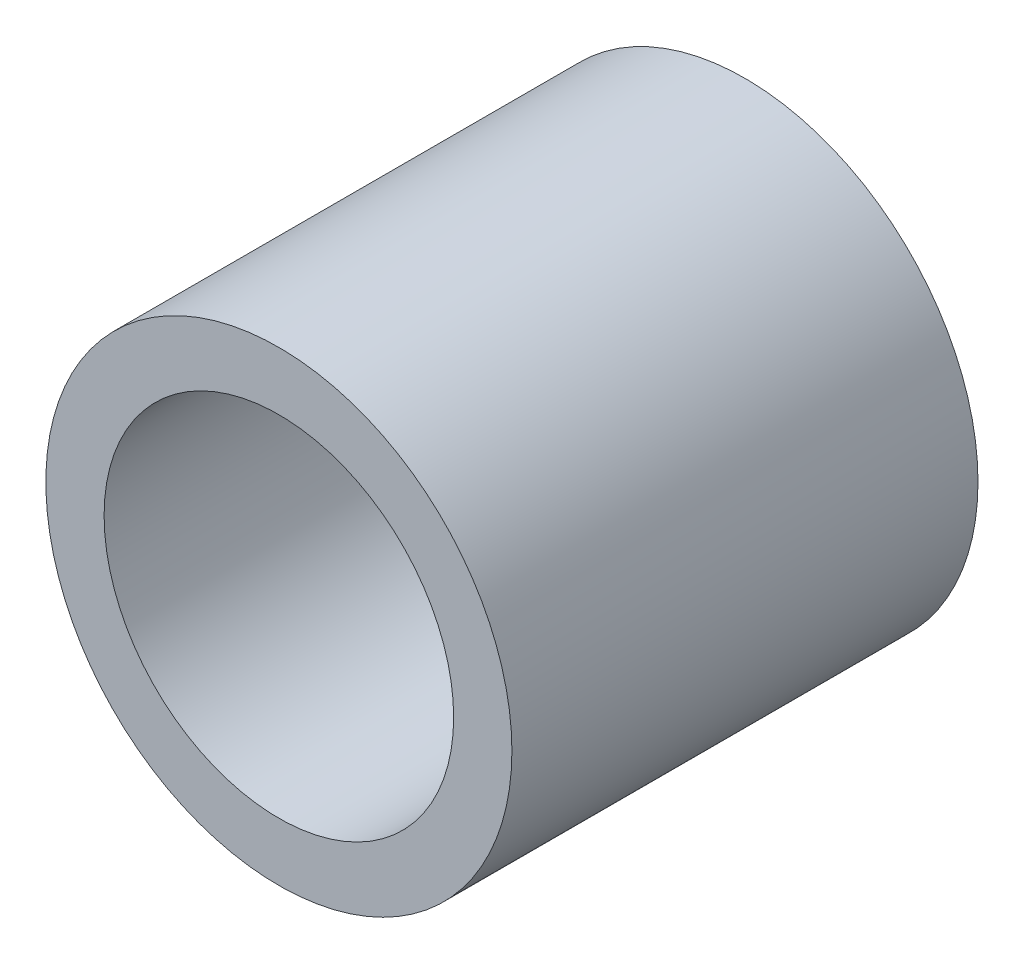
SolidWorks part; units mm, degrees
ref_plane "前视基准面" through (0, 0, 0) normal (0, 0, 1) x (1, 0, 0)
ref_plane "上视基准面" through (0, 0, 0) normal (0, 1, 0) x (1, 0, 0)
ref_plane "右视基准面" through (0, 0, 0) normal (1, 0, 0) x (0, 0, -1)
other "Configuration Table"
sketch "草图1" plane through (0, 0, 0) normal (0, 0, 1) x (1, 0, 0)
  circle A0 centre (0, 0) radius 3
  circle A1 centre (0, 0) radius 4
  dimension "D1" = 6
  dimension "D2" = 8
extrude "凸台-拉伸1" add sketch "草图1" along normal blind 8
